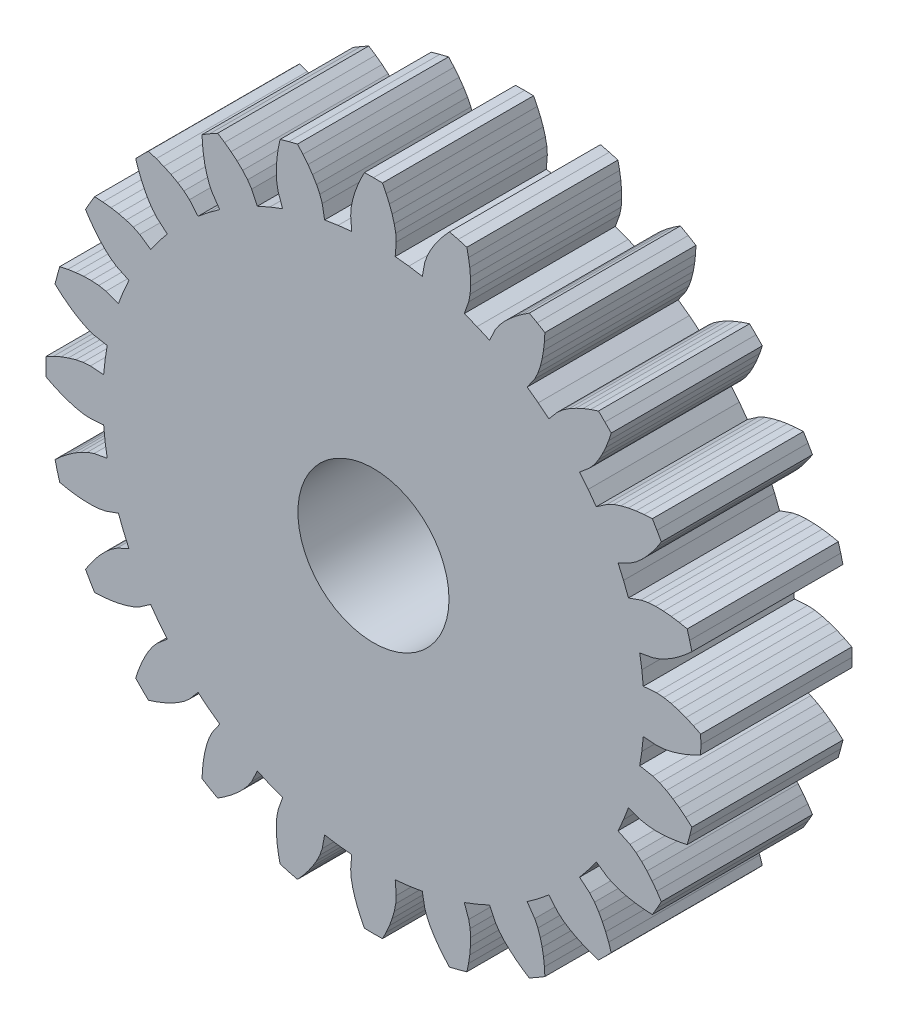
SolidWorks part; units mm, degrees
ref_plane "前视基准面" through (0, 0, 0) normal (0, 0, 1) x (1, 0, 0)
ref_plane "上视基准面" through (0, 0, 0) normal (0, 1, 0) x (1, 0, 0)
ref_plane "右视基准面" through (0, 0, 0) normal (1, 0, 0) x (0, 0, -1)
other "Configuration Table"
sketch "草图1" plane through (0, 0, 0) normal (0, 0, 1) x (1, 0, 0)
  line L0 (21.4306, -1.7258) -> (22.4799, -1.8102)
  line L1 (22.4799, -1.8102) -> (23.0594, -1.769)
  line L2 (23.0594, -1.769) -> (23.6441, -1.6519)
  line L3 (23.6441, -1.6519) -> (24.231, -1.482)
  line L4 (24.231, -1.482) -> (24.8186, -1.2668)
  line L5 (24.8186, -1.2668) -> (25.4054, -1.0105)
  line L6 (25.4054, -1.0105) -> (25.9902, -0.7155)
  line L7 (25.9902, -0.7155) -> (26, 0)
  line L8 (26, 0) -> (25.9902, 0.7155)
  line L9 (25.9902, 0.7155) -> (25.4054, 1.0105)
  line L10 (25.4054, 1.0105) -> (24.8186, 1.2668)
  line L11 (24.8186, 1.2668) -> (24.231, 1.482)
  line L12 (24.231, 1.482) -> (23.6441, 1.6519)
  line L13 (23.6441, 1.6519) -> (23.0594, 1.769)
  line L14 (23.0594, 1.769) -> (22.4799, 1.8102)
  line L15 (22.4799, 1.8102) -> (21.4306, 1.7258)
  line L16 (21.4306, 1.7258) -> (21.3161, 2.8063)
  line L17 (21.3161, 2.8063) -> (21.1471, 3.8797)
  line L18 (21.1471, 3.8797) -> (22.1824, 4.0696)
  line L19 (22.1824, 4.0696) -> (22.7315, 4.2595)
  line L20 (22.7315, 4.2595) -> (23.266, 4.524)
  line L21 (23.266, 4.524) -> (23.7889, 4.84)
  line L22 (23.7889, 4.84) -> (24.3008, 5.1999)
  line L23 (24.3008, 5.1999) -> (24.8012, 5.5994)
  line L24 (24.8012, 5.5994) -> (25.2897, 6.0357)
  line L25 (25.2897, 6.0357) -> (25.1141, 6.7293)
  line L26 (25.1141, 6.7293) -> (24.9194, 7.4178)
  line L27 (24.9194, 7.4178) -> (24.2782, 7.5514)
  line L28 (24.2782, 7.5514) -> (23.645, 7.6472)
  line L29 (23.645, 7.6472) -> (23.0218, 7.7029)
  line L30 (23.0218, 7.7029) -> (22.4109, 7.7151)
  line L31 (22.4109, 7.7151) -> (21.8159, 7.6769)
  line L32 (21.8159, 7.6769) -> (21.2453, 7.5668)
  line L33 (21.2453, 7.5668) -> (20.2537, 7.2136)
  line L34 (20.2537, 7.2136) -> (19.8634, 8.2277)
  line L35 (19.8634, 8.2277) -> (19.4223, 9.2208)
  line L36 (19.4223, 9.2208) -> (20.3732, 9.6722)
  line L37 (20.3732, 9.6722) -> (20.8545, 9.9977)
  line L38 (20.8545, 9.9977) -> (21.3023, 10.3915)
  line L39 (21.3023, 10.3915) -> (21.7257, 10.8321)
  line L40 (21.7257, 10.8321) -> (22.1269, 11.3122)
  line L41 (22.1269, 11.3122) -> (22.5069, 11.8276)
  line L42 (22.5069, 11.8276) -> (22.8659, 12.3755)
  line L43 (22.8659, 12.3755) -> (22.5167, 13)
  line L44 (22.5167, 13) -> (22.1504, 13.6147)
  line L45 (22.1504, 13.6147) -> (21.4965, 13.5778)
  line L46 (21.4965, 13.5778) -> (20.8601, 13.5064)
  line L47 (20.8601, 13.5064) -> (20.2437, 13.3989)
  line L48 (20.2437, 13.3989) -> (19.6505, 13.2526)
  line L49 (19.6505, 13.2526) -> (19.0856, 13.0617)
  line L50 (19.0856, 13.0617) -> (18.563, 12.8076)
  line L51 (18.563, 12.8076) -> (17.6966, 12.2099)
  line L52 (17.6966, 12.2099) -> (17.0571, 13.0884)
  line L53 (17.0571, 13.0884) -> (16.374, 13.9334)
  line L54 (16.374, 13.9334) -> (17.1757, 14.6156)
  line L55 (17.1757, 14.6156) -> (17.5563, 15.0546)
  line L56 (17.5563, 15.0546) -> (17.887, 15.5509)
  line L57 (17.887, 15.5509) -> (18.1818, 16.086)
  line L58 (18.1818, 16.086) -> (18.4452, 16.6536)
  line L59 (18.4452, 16.6536) -> (18.6788, 17.2498)
  line L60 (18.6788, 17.2498) -> (18.8837, 17.8719)
  line L61 (18.8837, 17.8719) -> (18.3848, 18.3848)
  line L62 (18.3848, 18.3848) -> (17.8719, 18.8837)
  line L63 (17.8719, 18.8837) -> (17.2498, 18.6788)
  line L64 (17.2498, 18.6788) -> (16.6536, 18.4452)
  line L65 (16.6536, 18.4452) -> (16.086, 18.1818)
  line L66 (16.086, 18.1818) -> (15.5509, 17.887)
  line L67 (15.5509, 17.887) -> (15.0546, 17.5563)
  line L68 (15.0546, 17.5563) -> (14.6156, 17.1757)
  line L69 (14.6156, 17.1757) -> (13.9334, 16.374)
  line L70 (13.9334, 16.374) -> (13.0884, 17.0571)
  line L71 (13.0884, 17.0571) -> (12.2099, 17.6966)
  line L72 (12.2099, 17.6966) -> (12.8076, 18.563)
  line L73 (12.8076, 18.563) -> (13.0617, 19.0856)
  line L74 (13.0617, 19.0856) -> (13.2526, 19.6505)
  line L75 (13.2526, 19.6505) -> (13.3989, 20.2437)
  line L76 (13.3989, 20.2437) -> (13.5064, 20.8601)
  line L77 (13.5064, 20.8601) -> (13.5778, 21.4965)
  line L78 (13.5778, 21.4965) -> (13.6147, 22.1504)
  line L79 (13.6147, 22.1504) -> (13, 22.5167)
  line L80 (13, 22.5167) -> (12.3755, 22.8659)
  line L81 (12.3755, 22.8659) -> (11.8276, 22.5069)
  line L82 (11.8276, 22.5069) -> (11.3122, 22.1269)
  line L83 (11.3122, 22.1269) -> (10.8321, 21.7257)
  line L84 (10.8321, 21.7257) -> (10.3915, 21.3023)
  line L85 (10.3915, 21.3023) -> (9.9977, 20.8545)
  line L86 (9.9977, 20.8545) -> (9.6722, 20.3732)
  line L87 (9.6722, 20.3732) -> (9.2208, 19.4223)
  line L88 (9.2208, 19.4223) -> (8.2277, 19.8634)
  line L89 (8.2277, 19.8634) -> (7.2136, 20.2537)
  line L90 (7.2136, 20.2537) -> (7.5668, 21.2453)
  line L91 (7.5668, 21.2453) -> (7.6769, 21.8159)
  line L92 (7.6769, 21.8159) -> (7.7151, 22.4109)
  line L93 (7.7151, 22.4109) -> (7.7029, 23.0218)
  line L94 (7.7029, 23.0218) -> (7.6472, 23.645)
  line L95 (7.6472, 23.645) -> (7.5514, 24.2782)
  line L96 (7.5514, 24.2782) -> (7.4178, 24.9194)
  line L97 (7.4178, 24.9194) -> (6.7293, 25.1141)
  line L98 (6.7293, 25.1141) -> (6.0357, 25.2897)
  line L99 (6.0357, 25.2897) -> (5.5994, 24.8012)
  line L100 (5.5994, 24.8012) -> (5.1999, 24.3008)
  line L101 (5.1999, 24.3008) -> (4.84, 23.7889)
  line L102 (4.84, 23.7889) -> (4.524, 23.266)
  line L103 (4.524, 23.266) -> (4.2595, 22.7315)
  line L104 (4.2595, 22.7315) -> (4.0696, 22.1824)
  line L105 (4.0696, 22.1824) -> (3.8797, 21.1471)
  line L106 (3.8797, 21.1471) -> (2.8063, 21.3161)
  line L107 (2.8063, 21.3161) -> (1.7258, 21.4306)
  line L108 (1.7258, 21.4306) -> (1.8102, 22.4799)
  line L109 (1.8102, 22.4799) -> (1.769, 23.0594)
  line L110 (1.769, 23.0594) -> (1.6519, 23.6441)
  line L111 (1.6519, 23.6441) -> (1.482, 24.231)
  line L112 (1.482, 24.231) -> (1.2668, 24.8186)
  line L113 (1.2668, 24.8186) -> (1.0105, 25.4054)
  line L114 (1.0105, 25.4054) -> (0.7155, 25.9902)
  line L115 (0.7155, 25.9902) -> (0, 26)
  line L116 (0, 26) -> (-0.7155, 25.9902)
  line L117 (-0.7155, 25.9902) -> (-1.0105, 25.4054)
  line L118 (-1.0105, 25.4054) -> (-1.2668, 24.8186)
  line L119 (-1.2668, 24.8186) -> (-1.482, 24.231)
  line L120 (-1.482, 24.231) -> (-1.6519, 23.6441)
  line L121 (-1.6519, 23.6441) -> (-1.769, 23.0594)
  line L122 (-1.769, 23.0594) -> (-1.8102, 22.4799)
  line L123 (-1.8102, 22.4799) -> (-1.7258, 21.4306)
  line L124 (-1.7258, 21.4306) -> (-2.8063, 21.3161)
  line L125 (-2.8063, 21.3161) -> (-3.8797, 21.1471)
  line L126 (-3.8797, 21.1471) -> (-4.0696, 22.1824)
  line L127 (-4.0696, 22.1824) -> (-4.2595, 22.7315)
  line L128 (-4.2595, 22.7315) -> (-4.524, 23.266)
  line L129 (-4.524, 23.266) -> (-4.84, 23.7889)
  line L130 (-4.84, 23.7889) -> (-5.1999, 24.3008)
  line L131 (-5.1999, 24.3008) -> (-5.5994, 24.8012)
  line L132 (-5.5994, 24.8012) -> (-6.0357, 25.2897)
  line L133 (-6.0357, 25.2897) -> (-6.7293, 25.1141)
  line L134 (-6.7293, 25.1141) -> (-7.4178, 24.9194)
  line L135 (-7.4178, 24.9194) -> (-7.5514, 24.2782)
  line L136 (-7.5514, 24.2782) -> (-7.6472, 23.645)
  line L137 (-7.6472, 23.645) -> (-7.7029, 23.0218)
  line L138 (-7.7029, 23.0218) -> (-7.7151, 22.4109)
  line L139 (-7.7151, 22.4109) -> (-7.6769, 21.8159)
  line L140 (-7.6769, 21.8159) -> (-7.5668, 21.2453)
  line L141 (-7.5668, 21.2453) -> (-7.2136, 20.2537)
  line L142 (-7.2136, 20.2537) -> (-8.2277, 19.8634)
  line L143 (-8.2277, 19.8634) -> (-9.2208, 19.4223)
  line L144 (-9.2208, 19.4223) -> (-9.6722, 20.3732)
  line L145 (-9.6722, 20.3732) -> (-9.9977, 20.8545)
  line L146 (-9.9977, 20.8545) -> (-10.3915, 21.3023)
  line L147 (-10.3915, 21.3023) -> (-10.8321, 21.7257)
  line L148 (-10.8321, 21.7257) -> (-11.3122, 22.1269)
  line L149 (-11.3122, 22.1269) -> (-11.8276, 22.5069)
  line L150 (-11.8276, 22.5069) -> (-12.3755, 22.8659)
  line L151 (-12.3755, 22.8659) -> (-13, 22.5167)
  line L152 (-13, 22.5167) -> (-13.6147, 22.1504)
  line L153 (-13.6147, 22.1504) -> (-13.5778, 21.4965)
  line L154 (-13.5778, 21.4965) -> (-13.5064, 20.8601)
  line L155 (-13.5064, 20.8601) -> (-13.3989, 20.2437)
  line L156 (-13.3989, 20.2437) -> (-13.2526, 19.6505)
  line L157 (-13.2526, 19.6505) -> (-13.0617, 19.0856)
  line L158 (-13.0617, 19.0856) -> (-12.8076, 18.563)
  line L159 (-12.8076, 18.563) -> (-12.2099, 17.6966)
  line L160 (-12.2099, 17.6966) -> (-13.0884, 17.0571)
  line L161 (-13.0884, 17.0571) -> (-13.9334, 16.374)
  line L162 (-13.9334, 16.374) -> (-14.6156, 17.1757)
  line L163 (-14.6156, 17.1757) -> (-15.0546, 17.5563)
  line L164 (-15.0546, 17.5563) -> (-15.5509, 17.887)
  line L165 (-15.5509, 17.887) -> (-16.086, 18.1818)
  line L166 (-16.086, 18.1818) -> (-16.6536, 18.4452)
  line L167 (-16.6536, 18.4452) -> (-17.2498, 18.6788)
  line L168 (-17.2498, 18.6788) -> (-17.8719, 18.8837)
  line L169 (-17.8719, 18.8837) -> (-18.3848, 18.3848)
  line L170 (-18.3848, 18.3848) -> (-18.8837, 17.8719)
  line L171 (-18.8837, 17.8719) -> (-18.6788, 17.2498)
  line L172 (-18.6788, 17.2498) -> (-18.4452, 16.6536)
  line L173 (-18.4452, 16.6536) -> (-18.1818, 16.086)
  line L174 (-18.1818, 16.086) -> (-17.887, 15.5509)
  line L175 (-17.887, 15.5509) -> (-17.5563, 15.0546)
  line L176 (-17.5563, 15.0546) -> (-17.1757, 14.6156)
  line L177 (-17.1757, 14.6156) -> (-16.374, 13.9334)
  line L178 (-16.374, 13.9334) -> (-17.0571, 13.0884)
  line L179 (-17.0571, 13.0884) -> (-17.6966, 12.2099)
  line L180 (-17.6966, 12.2099) -> (-18.563, 12.8076)
  line L181 (-18.563, 12.8076) -> (-19.0856, 13.0617)
  line L182 (-19.0856, 13.0617) -> (-19.6505, 13.2526)
  line L183 (-19.6505, 13.2526) -> (-20.2437, 13.3989)
  line L184 (-20.2437, 13.3989) -> (-20.8601, 13.5064)
  line L185 (-20.8601, 13.5064) -> (-21.4965, 13.5778)
  line L186 (-21.4965, 13.5778) -> (-22.1504, 13.6147)
  line L187 (-22.1504, 13.6147) -> (-22.5167, 13)
  line L188 (-22.5167, 13) -> (-22.8659, 12.3755)
  line L189 (-22.8659, 12.3755) -> (-22.5069, 11.8276)
  line L190 (-22.5069, 11.8276) -> (-22.1269, 11.3122)
  line L191 (-22.1269, 11.3122) -> (-21.7257, 10.8321)
  line L192 (-21.7257, 10.8321) -> (-21.3023, 10.3915)
  line L193 (-21.3023, 10.3915) -> (-20.8545, 9.9977)
  line L194 (-20.8545, 9.9977) -> (-20.3732, 9.6722)
  line L195 (-20.3732, 9.6722) -> (-19.4223, 9.2208)
  line L196 (-19.4223, 9.2208) -> (-19.8634, 8.2277)
  line L197 (-19.8634, 8.2277) -> (-20.2537, 7.2136)
  line L198 (-20.2537, 7.2136) -> (-21.2453, 7.5668)
  line L199 (-21.2453, 7.5668) -> (-21.8159, 7.6769)
  line L200 (-21.8159, 7.6769) -> (-22.4109, 7.7151)
  line L201 (-22.4109, 7.7151) -> (-23.0218, 7.7029)
  line L202 (-23.0218, 7.7029) -> (-23.645, 7.6472)
  line L203 (-23.645, 7.6472) -> (-24.2782, 7.5514)
  line L204 (-24.2782, 7.5514) -> (-24.9194, 7.4178)
  line L205 (-24.9194, 7.4178) -> (-25.1141, 6.7293)
  line L206 (-25.1141, 6.7293) -> (-25.2897, 6.0357)
  line L207 (-25.2897, 6.0357) -> (-24.8012, 5.5994)
  line L208 (-24.8012, 5.5994) -> (-24.3008, 5.1999)
  line L209 (-24.3008, 5.1999) -> (-23.7889, 4.84)
  line L210 (-23.7889, 4.84) -> (-23.266, 4.524)
  line L211 (-23.266, 4.524) -> (-22.7315, 4.2595)
  line L212 (-22.7315, 4.2595) -> (-22.1824, 4.0696)
  line L213 (-22.1824, 4.0696) -> (-21.1471, 3.8797)
  line L214 (-21.1471, 3.8797) -> (-21.3161, 2.8063)
  line L215 (-21.3161, 2.8063) -> (-21.4306, 1.7258)
  line L216 (-21.4306, 1.7258) -> (-22.4799, 1.8102)
  line L217 (-22.4799, 1.8102) -> (-23.0594, 1.769)
  line L218 (-23.0594, 1.769) -> (-23.6441, 1.6519)
  line L219 (-23.6441, 1.6519) -> (-24.231, 1.482)
  line L220 (-24.231, 1.482) -> (-24.8186, 1.2668)
  line L221 (-24.8186, 1.2668) -> (-25.4054, 1.0105)
  line L222 (-25.4054, 1.0105) -> (-25.9902, 0.7155)
  line L223 (-25.9902, 0.7155) -> (-26, 0)
  line L224 (-26, 0) -> (-25.9902, -0.7155)
  line L225 (-25.9902, -0.7155) -> (-25.4054, -1.0105)
  line L226 (-25.4054, -1.0105) -> (-24.8186, -1.2668)
  line L227 (-24.8186, -1.2668) -> (-24.231, -1.482)
  line L228 (-24.231, -1.482) -> (-23.6441, -1.6519)
  line L229 (-23.6441, -1.6519) -> (-23.0594, -1.769)
  line L230 (-23.0594, -1.769) -> (-22.4799, -1.8102)
  line L231 (-22.4799, -1.8102) -> (-21.4306, -1.7258)
  line L232 (-21.4306, -1.7258) -> (-21.3161, -2.8063)
  line L233 (-21.3161, -2.8063) -> (-21.1471, -3.8797)
  line L234 (-21.1471, -3.8797) -> (-22.1824, -4.0696)
  line L235 (-22.1824, -4.0696) -> (-22.7315, -4.2595)
  line L236 (-22.7315, -4.2595) -> (-23.266, -4.524)
  line L237 (-23.266, -4.524) -> (-23.7889, -4.84)
  line L238 (-23.7889, -4.84) -> (-24.3008, -5.1999)
  line L239 (-24.3008, -5.1999) -> (-24.8012, -5.5994)
  line L240 (-24.8012, -5.5994) -> (-25.2897, -6.0357)
  line L241 (-25.2897, -6.0357) -> (-25.1141, -6.7293)
  line L242 (-25.1141, -6.7293) -> (-24.9194, -7.4178)
  line L243 (-24.9194, -7.4178) -> (-24.2782, -7.5514)
  line L244 (-24.2782, -7.5514) -> (-23.645, -7.6472)
  line L245 (-23.645, -7.6472) -> (-23.0218, -7.7029)
  line L246 (-23.0218, -7.7029) -> (-22.4109, -7.7151)
  line L247 (-22.4109, -7.7151) -> (-21.8159, -7.6769)
  line L248 (-21.8159, -7.6769) -> (-21.2453, -7.5668)
  line L249 (-21.2453, -7.5668) -> (-20.2537, -7.2136)
  line L250 (-20.2537, -7.2136) -> (-19.8634, -8.2277)
  line L251 (-19.8634, -8.2277) -> (-19.4223, -9.2208)
  line L252 (-19.4223, -9.2208) -> (-20.3732, -9.6722)
  line L253 (-20.3732, -9.6722) -> (-20.8545, -9.9977)
  line L254 (-20.8545, -9.9977) -> (-21.3023, -10.3915)
  line L255 (-21.3023, -10.3915) -> (-21.7257, -10.8321)
  line L256 (-21.7257, -10.8321) -> (-22.1269, -11.3122)
  line L257 (-22.1269, -11.3122) -> (-22.5069, -11.8276)
  line L258 (-22.5069, -11.8276) -> (-22.8659, -12.3755)
  line L259 (-22.8659, -12.3755) -> (-22.5167, -13)
  line L260 (-22.5167, -13) -> (-22.1504, -13.6147)
  line L261 (-22.1504, -13.6147) -> (-21.4965, -13.5778)
  line L262 (-21.4965, -13.5778) -> (-20.8601, -13.5064)
  line L263 (-20.8601, -13.5064) -> (-20.2437, -13.3989)
  line L264 (-20.2437, -13.3989) -> (-19.6505, -13.2526)
  line L265 (-19.6505, -13.2526) -> (-19.0856, -13.0617)
  line L266 (-19.0856, -13.0617) -> (-18.563, -12.8076)
  line L267 (-18.563, -12.8076) -> (-17.6966, -12.2099)
  line L268 (-17.6966, -12.2099) -> (-17.0571, -13.0884)
  line L269 (-17.0571, -13.0884) -> (-16.374, -13.9334)
  line L270 (-16.374, -13.9334) -> (-17.1757, -14.6156)
  line L271 (-17.1757, -14.6156) -> (-17.5563, -15.0546)
  line L272 (-17.5563, -15.0546) -> (-17.887, -15.5509)
  line L273 (-17.887, -15.5509) -> (-18.1818, -16.086)
  line L274 (-18.1818, -16.086) -> (-18.4452, -16.6536)
  line L275 (-18.4452, -16.6536) -> (-18.6788, -17.2498)
  line L276 (-18.6788, -17.2498) -> (-18.8837, -17.8719)
  line L277 (-18.8837, -17.8719) -> (-18.3848, -18.3848)
  line L278 (-18.3848, -18.3848) -> (-17.8719, -18.8837)
  line L279 (-17.8719, -18.8837) -> (-17.2498, -18.6788)
  line L280 (-17.2498, -18.6788) -> (-16.6536, -18.4452)
  line L281 (-16.6536, -18.4452) -> (-16.086, -18.1818)
  line L282 (-16.086, -18.1818) -> (-15.5509, -17.887)
  line L283 (-15.5509, -17.887) -> (-15.0546, -17.5563)
  line L284 (-15.0546, -17.5563) -> (-14.6156, -17.1757)
  line L285 (-14.6156, -17.1757) -> (-13.9334, -16.374)
  line L286 (-13.9334, -16.374) -> (-13.0884, -17.0571)
  line L287 (-13.0884, -17.0571) -> (-12.2099, -17.6966)
  line L288 (-12.2099, -17.6966) -> (-12.8076, -18.563)
  line L289 (-12.8076, -18.563) -> (-13.0617, -19.0856)
  line L290 (-13.0617, -19.0856) -> (-13.2526, -19.6505)
  line L291 (-13.2526, -19.6505) -> (-13.3989, -20.2437)
  line L292 (-13.3989, -20.2437) -> (-13.5064, -20.8601)
  line L293 (-13.5064, -20.8601) -> (-13.5778, -21.4965)
  line L294 (-13.5778, -21.4965) -> (-13.6147, -22.1504)
  line L295 (-13.6147, -22.1504) -> (-13, -22.5167)
  line L296 (-13, -22.5167) -> (-12.3755, -22.8659)
  line L297 (-12.3755, -22.8659) -> (-11.8276, -22.5069)
  line L298 (-11.8276, -22.5069) -> (-11.3122, -22.1269)
  line L299 (-11.3122, -22.1269) -> (-10.8321, -21.7257)
  line L300 (-10.8321, -21.7257) -> (-10.3915, -21.3023)
  line L301 (-10.3915, -21.3023) -> (-9.9977, -20.8545)
  line L302 (-9.9977, -20.8545) -> (-9.6722, -20.3732)
  line L303 (-9.6722, -20.3732) -> (-9.2208, -19.4223)
  line L304 (-9.2208, -19.4223) -> (-8.2277, -19.8634)
  line L305 (-8.2277, -19.8634) -> (-7.2136, -20.2537)
  line L306 (-7.2136, -20.2537) -> (-7.5668, -21.2453)
  line L307 (-7.5668, -21.2453) -> (-7.6769, -21.8159)
  line L308 (-7.6769, -21.8159) -> (-7.7151, -22.4109)
  line L309 (-7.7151, -22.4109) -> (-7.7029, -23.0218)
  line L310 (-7.7029, -23.0218) -> (-7.6472, -23.645)
  line L311 (-7.6472, -23.645) -> (-7.5514, -24.2782)
  line L312 (-7.5514, -24.2782) -> (-7.4178, -24.9194)
  line L313 (-7.4178, -24.9194) -> (-6.7293, -25.1141)
  line L314 (-6.7293, -25.1141) -> (-6.0357, -25.2897)
  line L315 (-6.0357, -25.2897) -> (-5.5994, -24.8012)
  line L316 (-5.5994, -24.8012) -> (-5.1999, -24.3008)
  line L317 (-5.1999, -24.3008) -> (-4.84, -23.7889)
  line L318 (-4.84, -23.7889) -> (-4.524, -23.266)
  line L319 (-4.524, -23.266) -> (-4.2595, -22.7315)
  line L320 (-4.2595, -22.7315) -> (-4.0696, -22.1824)
  line L321 (-4.0696, -22.1824) -> (-3.8797, -21.1471)
  line L322 (-3.8797, -21.1471) -> (-2.8063, -21.3161)
  line L323 (-2.8063, -21.3161) -> (-1.7258, -21.4306)
  line L324 (-1.7258, -21.4306) -> (-1.8102, -22.4799)
  line L325 (-1.8102, -22.4799) -> (-1.769, -23.0594)
  line L326 (-1.769, -23.0594) -> (-1.6519, -23.6441)
  line L327 (-1.6519, -23.6441) -> (-1.482, -24.231)
  line L328 (-1.482, -24.231) -> (-1.2668, -24.8186)
  line L329 (-1.2668, -24.8186) -> (-1.0105, -25.4054)
  line L330 (-1.0105, -25.4054) -> (-0.7155, -25.9902)
  line L331 (-0.7155, -25.9902) -> (0, -26)
  line L332 (0, -26) -> (0.7155, -25.9902)
  line L333 (0.7155, -25.9902) -> (1.0105, -25.4054)
  line L334 (1.0105, -25.4054) -> (1.2668, -24.8186)
  line L335 (1.2668, -24.8186) -> (1.482, -24.231)
  line L336 (1.482, -24.231) -> (1.6519, -23.6441)
  line L337 (1.6519, -23.6441) -> (1.769, -23.0594)
  line L338 (1.769, -23.0594) -> (1.8102, -22.4799)
  line L339 (1.8102, -22.4799) -> (1.7258, -21.4306)
  line L340 (1.7258, -21.4306) -> (2.8063, -21.3161)
  line L341 (2.8063, -21.3161) -> (3.8797, -21.1471)
  line L342 (3.8797, -21.1471) -> (4.0696, -22.1824)
  line L343 (4.0696, -22.1824) -> (4.2595, -22.7315)
  line L344 (4.2595, -22.7315) -> (4.524, -23.266)
  line L345 (4.524, -23.266) -> (4.84, -23.7889)
  line L346 (4.84, -23.7889) -> (5.1999, -24.3008)
  line L347 (5.1999, -24.3008) -> (5.5994, -24.8012)
  line L348 (5.5994, -24.8012) -> (6.0357, -25.2897)
  line L349 (6.0357, -25.2897) -> (6.7293, -25.1141)
  line L350 (6.7293, -25.1141) -> (7.4178, -24.9194)
  line L351 (7.4178, -24.9194) -> (7.5514, -24.2782)
  line L352 (7.5514, -24.2782) -> (7.6472, -23.645)
  line L353 (7.6472, -23.645) -> (7.7029, -23.0218)
  line L354 (7.7029, -23.0218) -> (7.7151, -22.4109)
  line L355 (7.7151, -22.4109) -> (7.6769, -21.8159)
  line L356 (7.6769, -21.8159) -> (7.5668, -21.2453)
  line L357 (7.5668, -21.2453) -> (7.2136, -20.2537)
  line L358 (7.2136, -20.2537) -> (8.2277, -19.8634)
  line L359 (8.2277, -19.8634) -> (9.2208, -19.4223)
  line L360 (9.2208, -19.4223) -> (9.6722, -20.3732)
  line L361 (9.6722, -20.3732) -> (9.9977, -20.8545)
  line L362 (9.9977, -20.8545) -> (10.3915, -21.3023)
  line L363 (10.3915, -21.3023) -> (10.8321, -21.7257)
  line L364 (10.8321, -21.7257) -> (11.3122, -22.1269)
  line L365 (11.3122, -22.1269) -> (11.8276, -22.5069)
  line L366 (11.8276, -22.5069) -> (12.3755, -22.8659)
  line L367 (12.3755, -22.8659) -> (13, -22.5167)
  line L368 (13, -22.5167) -> (13.6147, -22.1504)
  line L369 (13.6147, -22.1504) -> (13.5778, -21.4965)
  line L370 (13.5778, -21.4965) -> (13.5064, -20.8601)
  line L371 (13.5064, -20.8601) -> (13.3989, -20.2437)
  line L372 (13.3989, -20.2437) -> (13.2526, -19.6505)
  line L373 (13.2526, -19.6505) -> (13.0617, -19.0856)
  line L374 (13.0617, -19.0856) -> (12.8076, -18.563)
  line L375 (12.8076, -18.563) -> (12.2099, -17.6966)
  line L376 (12.2099, -17.6966) -> (13.0884, -17.0571)
  line L377 (13.0884, -17.0571) -> (13.9334, -16.374)
  line L378 (13.9334, -16.374) -> (14.6156, -17.1757)
  line L379 (14.6156, -17.1757) -> (15.0546, -17.5563)
  line L380 (15.0546, -17.5563) -> (15.5509, -17.887)
  line L381 (15.5509, -17.887) -> (16.086, -18.1818)
  line L382 (16.086, -18.1818) -> (16.6536, -18.4452)
  line L383 (16.6536, -18.4452) -> (17.2498, -18.6788)
  line L384 (17.2498, -18.6788) -> (17.8719, -18.8837)
  line L385 (17.8719, -18.8837) -> (18.3848, -18.3848)
  line L386 (18.3848, -18.3848) -> (18.8837, -17.8719)
  line L387 (18.8837, -17.8719) -> (18.6788, -17.2498)
  line L388 (18.6788, -17.2498) -> (18.4452, -16.6536)
  line L389 (18.4452, -16.6536) -> (18.1818, -16.086)
  line L390 (18.1818, -16.086) -> (17.887, -15.5509)
  line L391 (17.887, -15.5509) -> (17.5563, -15.0546)
  line L392 (17.5563, -15.0546) -> (17.1757, -14.6156)
  line L393 (17.1757, -14.6156) -> (16.374, -13.9334)
  line L394 (16.374, -13.9334) -> (17.0571, -13.0884)
  line L395 (17.0571, -13.0884) -> (17.6966, -12.2099)
  line L396 (17.6966, -12.2099) -> (18.563, -12.8076)
  line L397 (18.563, -12.8076) -> (19.0856, -13.0617)
  line L398 (19.0856, -13.0617) -> (19.6505, -13.2526)
  line L399 (19.6505, -13.2526) -> (20.2437, -13.3989)
  line L400 (20.2437, -13.3989) -> (20.8601, -13.5064)
  line L401 (20.8601, -13.5064) -> (21.4965, -13.5778)
  line L402 (21.4965, -13.5778) -> (22.1504, -13.6147)
  line L403 (22.1504, -13.6147) -> (22.5167, -13)
  line L404 (22.5167, -13) -> (22.8659, -12.3755)
  line L405 (22.8659, -12.3755) -> (22.5069, -11.8276)
  line L406 (22.5069, -11.8276) -> (22.1269, -11.3122)
  line L407 (22.1269, -11.3122) -> (21.7257, -10.8321)
  line L408 (21.7257, -10.8321) -> (21.3023, -10.3915)
  line L409 (21.3023, -10.3915) -> (20.8545, -9.9977)
  line L410 (20.8545, -9.9977) -> (20.3732, -9.6722)
  line L411 (20.3732, -9.6722) -> (19.4223, -9.2208)
  line L412 (19.4223, -9.2208) -> (19.8634, -8.2277)
  line L413 (19.8634, -8.2277) -> (20.2537, -7.2136)
  line L414 (20.2537, -7.2136) -> (21.2453, -7.5668)
  line L415 (21.2453, -7.5668) -> (21.8159, -7.6769)
  line L416 (21.8159, -7.6769) -> (22.4109, -7.7151)
  line L417 (22.4109, -7.7151) -> (23.0218, -7.7029)
  line L418 (23.0218, -7.7029) -> (23.645, -7.6472)
  line L419 (23.645, -7.6472) -> (24.2782, -7.5514)
  line L420 (24.2782, -7.5514) -> (24.9194, -7.4178)
  line L421 (24.9194, -7.4178) -> (25.1141, -6.7293)
  line L422 (25.1141, -6.7293) -> (25.2897, -6.0357)
  line L423 (25.2897, -6.0357) -> (24.8012, -5.5994)
  line L424 (24.8012, -5.5994) -> (24.3008, -5.1999)
  line L425 (24.3008, -5.1999) -> (23.7889, -4.84)
  line L426 (23.7889, -4.84) -> (23.266, -4.524)
  line L427 (23.266, -4.524) -> (22.7315, -4.2595)
  line L428 (22.7315, -4.2595) -> (22.1824, -4.0696)
  line L429 (22.1824, -4.0696) -> (21.1471, -3.8797)
  line L430 (21.1471, -3.8797) -> (21.3161, -2.8063)
  line L431 (21.3161, -2.8063) -> (21.4306, -1.7258)
  circle A0 centre (0, 0) radius 6
extrude "凸台-拉伸1" add sketch "草图1" along normal blind 12 from offset 22
